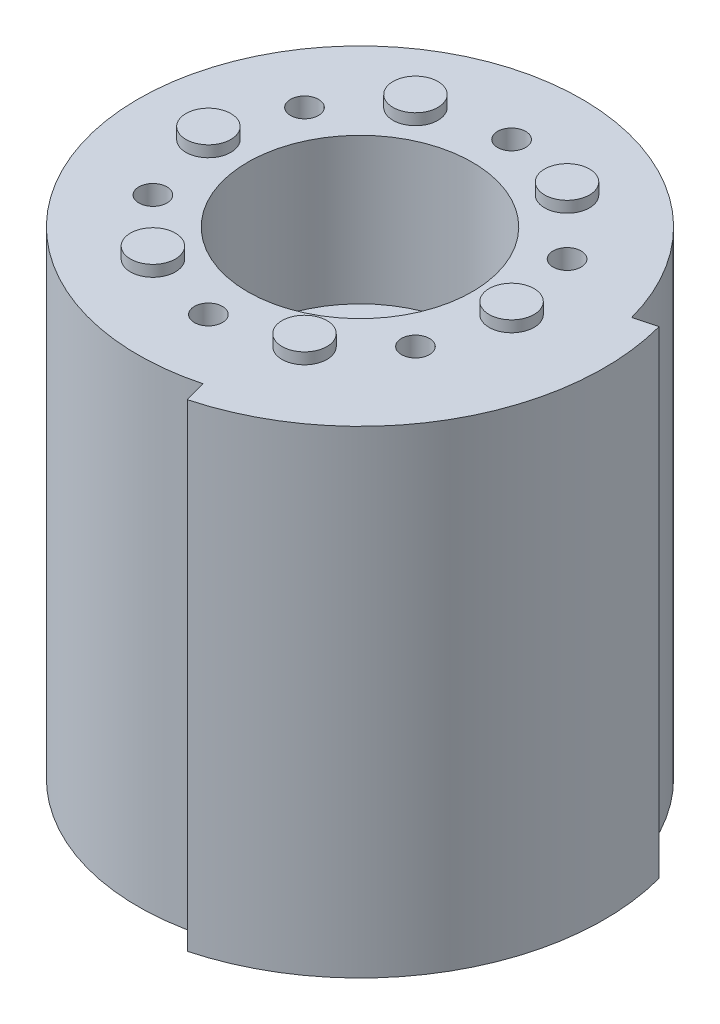
SolidWorks part; units mm, degrees
material "ABS"
ref_plane "前视基准面" through (0, 0, 0) normal (0, 0, 1) x (1, 0, 0)
ref_plane "上视基准面" through (0, 0, 0) normal (0, 1, 0) x (1, 0, 0)
ref_plane "右视基准面" through (0, 0, 0) normal (1, 0, 0) x (0, 0, -1)
other "Configuration Table"
sketch "草图1" plane through (0, 0, 0) normal (0, 1, 0) x (1, 0, 0)
  circle A0 centre (0, 0) radius 18.75
  circle A1 centre (0, 0) radius 19.75
  dimension "D1" = 37.5
  dimension "D2" = 1
extrude "凸台-拉伸1" add sketch "草图1" along normal blind 1
sketch "草图2" plane through (0, 1, 0) normal (0, 1, 0) x (1, 0, 0)
  circle A1 centre (0, 0) radius 19.75
  circle A2 centre (0, 0) radius 19.75
  dimension "D1" = 0
extrude "凸台-拉伸2" add sketch "草图2" along normal blind 41.8
sketch "草图3" plane through (0, 42.8, 0) normal (0, 1, 0) x (1, 0, 0)
  circle A0 centre (0, 0) radius 10
  circle A1 centre (0, 0) radius 13.5 construction
  circle A2 centre (0, 13.5) radius 1.25
  circle A3 centre (11.6913, 6.75) radius 1.25
  circle A4 centre (11.6913, -6.75) radius 1.25
  circle A5 centre (0, -13.5) radius 1.25
  circle A6 centre (-11.6913, -6.75) radius 1.25
  circle A7 centre (-11.6913, 6.75) radius 1.25
  point P18 (0, 0)
  dimension "D1" = 20
  dimension "D2" = 27
  dimension "D3" = 2.5
  dimension "D4" = 6
extrude "切除-拉伸1" cut sketch "草图3" against normal blind 13
sketch "草图4" plane through (0, 1, 0) normal (0, -1, 0) x (1, 0, 0)
  circle A0 centre (0, 0) radius 12 construction
  circle A1 centre (12, 0) radius 2
  circle A2 centre (-6, -10.3923) radius 2
  circle A3 centre (-6, 10.3923) radius 2
  dimension "D1" = 24
  dimension "D2" = 4
  dimension "D3" = 3
extrude "凸台-拉伸3" add sketch "草图4" along normal blind 1
sketch "草图5" plane through (0, 42.8, 0) normal (0, 1, 0) x (1, 0, 0)
  circle A0 centre (0, 0) radius 13.5 construction
  circle A1 centre (13.5, 0) radius 2
  circle A2 centre (6.75, -11.6913) radius 2
  circle A3 centre (-6.75, -11.6913) radius 2
  circle A4 centre (-13.5, 0) radius 2
  circle A5 centre (-6.75, 11.6913) radius 2
  circle A6 centre (6.75, 11.6913) radius 2
  dimension "D1" = 27
  dimension "D2" = 4
  dimension "D3" = 6
extrude "凸台-拉伸4" add sketch "草图5" along normal blind 1
sketch "草图6" plane through (0, 1, 0) normal (0, -1, 0) x (1, 0, 0)
  circle A0 centre (-13.5, 0) radius 3
  circle A1 centre (6.75, 11.6913) radius 3
  circle A2 centre (6.75, -11.6913) radius 3
  point P10 (0, 0)
  dimension "D1" = 6
  dimension "D2" = 13.5
extrude "切除-拉伸2" cut sketch "草图6" against normal blind 6
sketch "草图7" plane through (0, 42.8, 0) normal (0, 1, 0) x (1, 0, 0)
  line L0 (21.0089, 5.6293) -> (0, 0)
  line L1 (0, 0) -> (5.6293, -21.0089)
  line L2 (0, 0) -> (18.8361, -10.875) construction
  line L3 (0, 0) -> (21.75, 0) construction
  circle A0 centre (0, 0) radius 19.75 construction
  circle A1 centre (0, 0) radius 19.75
  circle A2 centre (0, 0) radius 21.75
  circle M17 centre (0, 0) radius 19.75
  dimension "D1" = 43.5
  dimension "D2" = 45
  dimension "D3" = 45
  dimension "D4" = 30
extrude "凸台-拉伸5" add sketch "草图7" against normal up to surface (42.8 mm away) contours L1 A2 L0 M17
sketch "草图9" plane through (0, 0, 0) normal (0, -1, 0) x (1, 0, 0)
  circle A0 centre (0, 0) radius 25
  dimension "D1" = 50
extrude "切除-拉伸4" cut sketch "草图9" against normal blind 0.25
